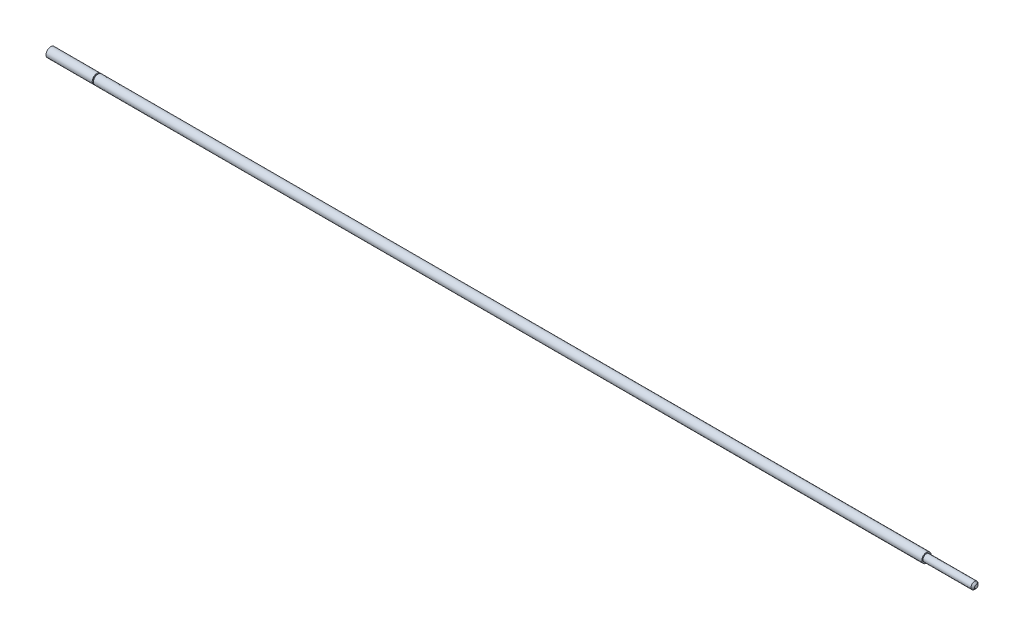
SolidWorks part; units mm, degrees
ref_plane "前视" through (0, 0, 0) normal (0, 0, 1) x (1, 0, 0)
ref_plane "上视" through (0, 0, 0) normal (0, 1, 0) x (1, 0, 0)
ref_plane "右视" through (0, 0, 0) normal (1, 0, 0) x (0, 0, -1)
sketch "草图1" plane through (0, 0, 0) normal (1, 0, 0) x (0, 0, -1)
  circle A0 centre (0, 0) radius 4
  dimension "D1" = 8
extrude "凸台-拉伸1" add sketch "草图1" along normal blind 39.5
sketch "草图2" plane through (39.5, 0, 0) normal (1, 0, 0) x (0, 0, -1)
  circle A0 centre (0, 0) radius 3
  dimension "D1" = 6
extrude "凸台-拉伸2" add sketch "草图2" along normal blind 1
sketch "草图3" plane through (40.5, 0, 0) normal (1, 0, 0) x (0, 0, -1)
  circle A0 centre (0, 0) radius 4
  dimension "D1" = 8
extrude "凸台-拉伸3" add sketch "草图3" along normal blind 707.5
sketch "草图4" plane through (748, 0, 0) normal (1, 0, 0) x (0, 0, -1)
  circle A0 centre (0, 0) radius 3
  dimension "D1" = 6
extrude "凸台-拉伸4" add sketch "草图4" along normal blind 42.5
chamfer "倒角1" distance 1.5 angle 45 1 edges at (790.5, 0, -3)
sketch "草图7" plane through (0, 0, 0) normal (-1, 0, 0) x (0, 0, 1)
  line L0 (-2.3816, 1.375) -> (-2.3816, -1.375)
  line L1 (-2.3816, -1.375) -> (0, -2.75)
  line L2 (0, -2.75) -> (2.3816, -1.375)
  line L3 (2.3816, -1.375) -> (2.3816, 1.375)
  line L4 (2.3816, 1.375) -> (0, 2.75)
  line L5 (0, 2.75) -> (-2.3816, 1.375)
  circle A0 centre (0, 0) radius 2.75 construction
  dimension "D1" = 5.5
extrude "切除-拉伸1" cut sketch "草图7" against normal blind 5
